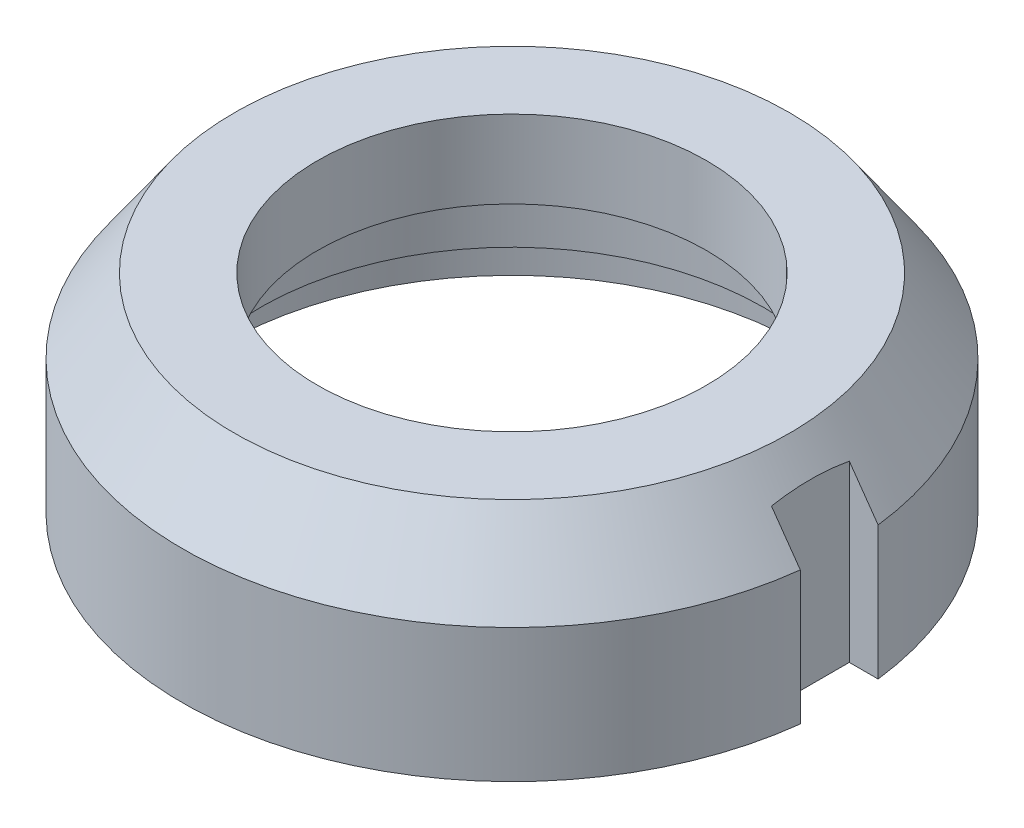
SolidWorks part; units mm, degrees
material "ABS"
ref_plane "Front Plane" through (0, 0, 0) normal (0, 0, 1) x (1, 0, 0)
ref_plane "Top Plane" through (0, 0, 0) normal (0, 1, 0) x (1, 0, 0)
ref_plane "Right Plane" through (0, 0, 0) normal (1, 0, 0) x (0, 0, -1)
sketch "Sketch1" plane through (0, 0, 0) normal (0, 0, 1) x (1, 0, 0)
  line L0 (0, 0) -> (0, 19.8374) construction
  line L1 (-9.7, 0) -> (-9.7, -2)
  line L2 (-10.7, 0) -> (-10.7, 19.8374) construction
  line L3 (-10.7, 0) -> (11.5, 0) construction
  line L5 (-9.7, 0) -> (-9.7, 3)
  line L6 (-9.7, 3) -> (-7.5, 3)
  line L7 (-7.5, 3) -> (-7.5, 6)
  line L8 (-7.5, 6) -> (-10.7, 6)
  line L9 (-10.7, 6) -> (-12.7, 3.1437)
  line L11 (-9.7, -2) -> (-12.7, -2)
  line L12 (-12.7, -2) -> (-12.7, 3.1437)
  dimension "D3" = 2.2
  dimension "D4" = 3
  dimension "D5" = 12.7
  dimension "D6" = 19.8374
  dimension "D7" = 35
  dimension "D8" = 3
  dimension "D9" = 6
  dimension "D10" = 2
  dimension "D1" = 9.7
  dimension "D11" = 2
  dimension "D2" = 10.7
revolve "Revolve1" add sketch "Sketch1" angle 360 about L0
sketch "Sketch4" plane through (0, -2, 0) normal (0, -1, 0) x (1, 0, 0)
  circle A0 centre (0, 0) radius 9.7 construction
  circle A1 centre (0, 0) radius 12.7
  circle A2 centre (0, 0) radius 12.7
  circle A3 centre (0, 0) radius 9.7
  circle A4 centre (0, 0) radius 11.2
  circle M2 centre (0, 0) radius 9.7
  dimension "D2" = 1.5
  dimension "D3" = 1.5
  dimension "D1" = 0
extrude "Cut-Extrude1" cut sketch "Sketch4" against normal blind 2 contours A4 M2
sketch "Sketch8" plane through (0, 6, 0) normal (0, 1, 0) x (1, 0, 0)
  line L0 (0, 0) -> (0, -12.7)
  line L1 (-11.5, 5.3889) -> (-11.5, -5.3889)
  line L2 (11.5, 5.3889) -> (11.5, -5.3889)
  line L3 (-11.5, 0) -> (-11.5, -12.7) construction
  line L4 (11.5, 0) -> (11.5, -12.7) construction
  line L5 (12.7, 0) -> (-12.7, 0) construction
  line L6 (12.7, 1.5) -> (11.5, 1.5)
  line L7 (12.7, -1.5) -> (11.5, -1.5)
  line L8 (-11.5, 1.5) -> (-12.7, 1.5)
  line L9 (-11.5, -1.5) -> (-12.7, -1.5)
  line L10 (12.7, 1.5) -> (-12.7, 1.5) construction
  line L12 (12.7, -1.5) -> (-12.7, -1.5) construction
  circle A0 centre (0, 0) radius 12.7 construction
  circle A1 centre (0, 0) radius 12.7
  dimension "D1" = 11.5
  dimension "D2" = 11.5
  dimension "D3" = 1.5
  dimension "D4" = 1.5
extrude "Cut-Extrude5" cut sketch "Sketch8" against normal through all contours L8 A1 L9 L1 | L7 A1 L6 L2
